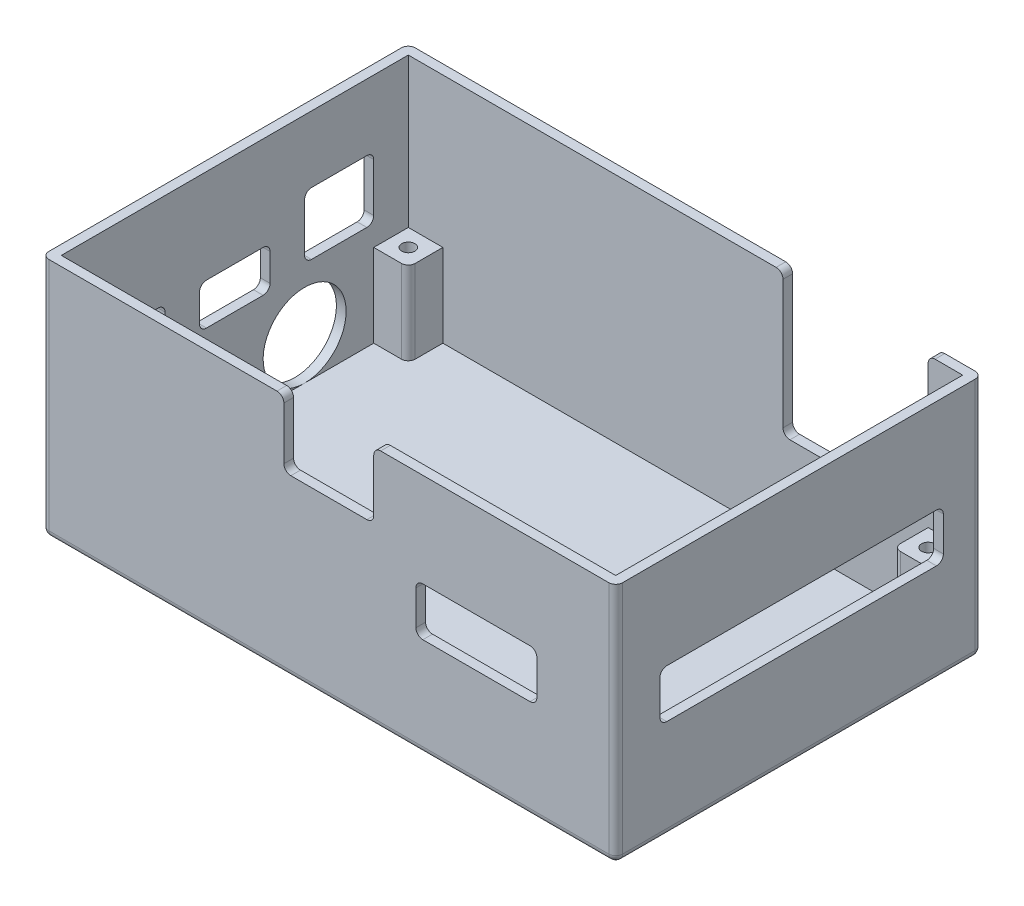
SolidWorks part; units mm, degrees
ref_plane "前视基准面" through (0, 0, 0) normal (0, 0, 1) x (1, 0, 0)
ref_plane "上视基准面" through (0, 0, 0) normal (0, 1, 0) x (1, 0, 0)
ref_plane "右视基准面" through (0, 0, 0) normal (1, 0, 0) x (0, 0, -1)
sketch "草图1" plane through (0, 0, 0) normal (0, 1, 0) x (1, 0, 0)
  line L1 (0, 0) -> (80.2, 0)
  line L2 (0, 0) -> (0, 50.2)
  line L3 (0, 50.2) -> (80.2, 50.2)
  line L4 (80.2, 0) -> (80.2, 50.2)
  line L5 (-1.4, -1.4) -> (81.6, -1.4)
  line L6 (-1.4, -1.4) -> (-1.4, 51.6)
  line L7 (-1.4, 51.6) -> (81.6, 51.6)
  line L8 (81.6, -1.4) -> (81.6, 51.6)
  dimension "D1" = 1.4
  dimension "D2" = 1.4
  dimension "D3" = 50.2
  dimension "D4" = 53
  dimension "D5" = 80.2
  dimension "D6" = 83
extrude "凸台-拉伸1" add sketch "草图1" along normal blind 35
sketch "草图3" plane through (0, 0, 0) normal (0, 1, 0) x (1, 0, 0)
  line L0 (-1.4, -1.4) -> (81.6, -1.4) construction
  line L1 (0, 50.2) -> (80.2, 50.2)
  line L2 (0, 50.2) -> (0, 0)
  line L3 (0, 0) -> (80.2, 0)
  line L4 (80.2, 50.2) -> (80.2, 0)
  line L5 (-1.4, 51.6) -> (-1.4, -1.4) construction
extrude "凸台-拉伸2" add sketch "草图3" along normal blind 1.4
sketch "草图4" plane through (0, 1.4, 0) normal (0, 1, 0) x (1, 0, 0)
  line L7 (0, 50.2) -> (0, 0) construction
  line L13 (0, 50.2) -> (5, 50.2)
  line L14 (0, 50.2) -> (0, 45.2)
  line L15 (0, 45.2) -> (5, 45.2)
  line L16 (5, 50.2) -> (5, 45.2)
  line L17 (0, 0) -> (5, 0)
  line L18 (0, 0) -> (0, 5)
  line L19 (0, 5) -> (5, 5)
  line L20 (5, 0) -> (5, 5)
  line L21 (80.2, 50.2) -> (75.2, 50.2)
  line L22 (80.2, 50.2) -> (80.2, 45.2)
  line L23 (80.2, 45.2) -> (75.2, 45.2)
  line L24 (75.2, 50.2) -> (75.2, 45.2)
  line L25 (80.2, 0) -> (75.2, 0)
  line L26 (80.2, 0) -> (80.2, 5)
  line L27 (80.2, 5) -> (75.2, 5)
  line L28 (75.2, 0) -> (75.2, 5)
  circle A0 centre (2.5, 2.5) radius 0.95
  circle A1 centre (77.7, 47.7) radius 0.95
  circle A2 centre (77.7, 2.1847) radius 0.95
  circle A3 centre (2.5, 47.7) radius 0.95
  point P32 (77.5587, 50.2)
  dimension "D3" = 1.9
  dimension "D1" = 1.9
  dimension "D2" = 1.9
  dimension "D4" = 2.5
  dimension "D5" = 2.5
  dimension "D6" = 5
  dimension "D7" = 5
  dimension "D8" = 5
  dimension "D9" = 5
  dimension "D10" = 5
  dimension "D11" = 5
  dimension "D12" = 5
  dimension "D13" = 5
  dimension "D14" = 2.5
  dimension "D15" = 2.5
  dimension "D16" = 2.5
  dimension "D17" = 2.5
  dimension "D18" = 2.5
extrude "凸台-拉伸3" add sketch "草图4" along normal blind 12
sketch "草图5" plane through (80.2, 0, 0) normal (-1, 0, 0) x (0, 0, 1)
  line L0 (-45.2, 13.4) -> (-50.2, 13.4) construction
  line L4 (0, 35) -> (0, 13.4) construction
  line L5 (-46, 14.4) -> (-5, 14.4)
  line L6 (-46, 14.4) -> (-46, 21.4)
  line L7 (-46, 21.4) -> (-5, 21.4)
  line L8 (-5, 14.4) -> (-5, 21.4)
  dimension "D1" = 1
  dimension "D4" = 5
extrude "切除-拉伸1" cut sketch "草图5" against normal blind 10
sketch "草图6" plane through (0, 0, 0) normal (1, 0, 0) x (0, 0, -1)
  line L0 (0, 35) -> (0, 13.4) construction
  line L1 (5, 14.4) -> (15, 14.4)
  line L2 (5, 14.4) -> (5, 21.4)
  line L3 (5, 21.4) -> (15, 21.4)
  line L4 (15, 14.4) -> (15, 21.4)
  line L5 (5, 13.4) -> (0, 13.4) construction
  line L6 (50.2, 35) -> (50.2, 13.4) construction
  line L7 (45.2, 16.4) -> (35.2, 16.4)
  line L8 (45.2, 16.4) -> (45.2, 25.4)
  line L9 (45.2, 25.4) -> (35.2, 25.4)
  line L10 (35.2, 16.4) -> (35.2, 25.4)
  line L11 (50.2, 13.4) -> (45.2, 13.4) construction
  line L13 (20, 15.4) -> (30.2, 15.4)
  line L14 (20, 15.4) -> (20, 21.4)
  line L15 (20, 21.4) -> (30.2, 21.4)
  line L16 (30.2, 15.4) -> (30.2, 21.4)
  dimension "D1" = 5
  dimension "D2" = 1
  dimension "D3" = 7
  dimension "D4" = 10
  dimension "D5" = 5
  dimension "D6" = 3
  dimension "D7" = 10
  dimension "D8" = 9
  dimension "D9" = 20
  dimension "D10" = 20
  dimension "D11" = 2
  dimension "D12" = 6
extrude "切除-拉伸2" cut sketch "草图6" against normal blind 10
sketch "草图8" plane through (0, 0, -50.2) normal (0, 0, 1) x (1, 0, 0)
  line L0 (80.2, 13.4) -> (75.2, 13.4) construction
  line L1 (75.2, 14.4) -> (54.2, 14.4)
  line L2 (75.2, 14.4) -> (75.2, 35.4)
  line L3 (75.2, 35.4) -> (54.2, 35.4)
  line L4 (54.2, 14.4) -> (54.2, 35.4)
  line L5 (75.2, 13.4) -> (75.2, 1.4) construction
  dimension "D1" = 1
  dimension "D2" = 0
  dimension "D3" = 21
  dimension "D4" = 21
extrude "切除-拉伸4" cut sketch "草图8" against normal blind 10
sketch "草图9" plane through (0, 0, 0) normal (0, 0, -1) x (-1, 0, 0)
  line L0 (0, 35) -> (-80.2, 35) construction
  line L1 (-46.6, 25.4) -> (-33.6, 25.4)
  line L2 (-46.6, 25.4) -> (-46.6, 35)
  line L3 (-46.6, 35) -> (-33.6, 35)
  line L4 (-33.6, 25.4) -> (-33.6, 35)
  line L5 (-75.2, 13.4) -> (-80.2, 13.4) construction
  line L7 (1.4, 35) -> (1.4, 0) construction
  dimension "D1" = 12
  dimension "D2" = 35
  dimension "D3" = 13
extrude "切除-拉伸5" cut sketch "草图9" against normal blind 10
fillet "圆角1" radius 1 23 edges at (54.2, 14.4, -50.9) (75.2, 14.4, -50.9) (46.6, 25.4, 0.7) (33.6, 25.4, 0.7) (80.9, 21.4, -46) (80.9, 21.4, -5) (80.9, 14.4, -5) (80.9, 14.4, -46) (-0.7, 21.4, -5) (-0.7, 21.4, -15) (-0.7, 14.4, -5) (-0.7, 14.4, -15) (-0.7, 15.4, -20) (-0.7, 15.4, -30.2) (-0.7, 21.4, -20) (-0.7, 25.4, -35.2) (-0.7, 16.4, -35.2) (-0.7, 16.4, -45.2) (-0.7, 25.4, -45.2) (5, 7.4, -45.2) (75.2, 7.4, -45.2) (5, 7.4, -5) (75.2, 7.4, -5)
fillet "圆角2" radius 1 8 edges at (-1.4, 17.5, -51.6) (40.1, 0, -51.6) (81.6, 17.5, -51.6) (81.6, 0, -25.1) (81.6, 17.5, 1.4) (40.1, 0, 1.4) (-1.4, 17.5, 1.4) (-1.4, 0, -25.1)
sketch "草图11" plane through (0, 0, 0) normal (0, 0, -1) x (-1, 0, 0)
  line L0 (-80.2, 35) -> (-80.2, 13.4) construction
  line L1 (-70.2, 14.4) -> (-52.6991, 14.4)
  line L2 (-70.2, 14.4) -> (-70.2, 21.4)
  line L3 (-70.2, 21.4) -> (-52.6991, 21.4)
  line L4 (-52.6991, 14.4) -> (-52.6991, 21.4)
  line L5 (-75.2, 13.4) -> (-80.2, 13.4) construction
  dimension "D1" = 10
  dimension "D2" = 1
  dimension "D3" = 7
extrude "切除-拉伸7" cut sketch "草图11" against normal blind 10
fillet "圆角5" radius 1 4 edges at (70.2, 21.4, 0.7) (52.6991, 14.4, 0.7) (70.2, 14.4, 0.7) (52.6991, 21.4, 0.7)
sketch "草图13" plane through (0, 0, 0) normal (1, 0, 0) x (0, 0, -1)
  line L0 (45.2, 1.4) -> (5, 1.4) construction
  line L1 (45.2, 13.4) -> (45.2, 1.4) construction
  circle A0 centre (35.2, 7.4) radius 6
  dimension "D1" = 6
  dimension "D3" = 12
  dimension "D2" = 10
extrude "切除-拉伸8" cut sketch "草图13" against normal blind 10
fillet "圆角6" radius 1 1 edges at (-0.7, 21.4, -30.2)
fillet "圆角7" radius 1 4 edges at (33.6, 35, 0.7) (46.6, 35, 0.7) (75.2, 35, -50.9) (54.2, 35, -50.9)
